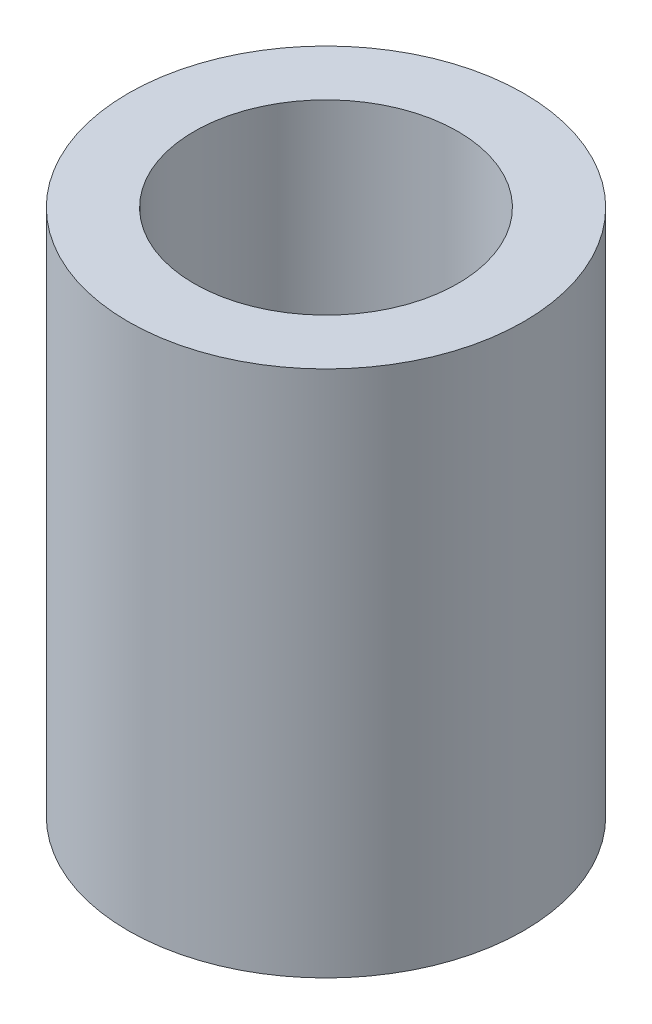
SolidWorks part; units mm, degrees
material "IGLIDUR G"
ref_plane "Front Plane" through (0, 0, 0) normal (0, 0, 1) x (1, 0, 0)
ref_plane "Top Plane" through (0, 0, 0) normal (0, 1, 0) x (1, 0, 0)
ref_plane "Right Plane" through (0, 0, 0) normal (1, 0, 0) x (0, 0, -1)
sketch "Sketch1" plane through (0, 0, 0) normal (0, 1, 0) x (1, 0, 0)
  circle A0 centre (0, 0) radius 1.5
  circle A1 centre (0, 0) radius 2.25
  dimension "D1" = 3
  dimension "D2" = 4.5
extrude "Boss-Extrude1" add sketch "Sketch1" along normal blind 6
